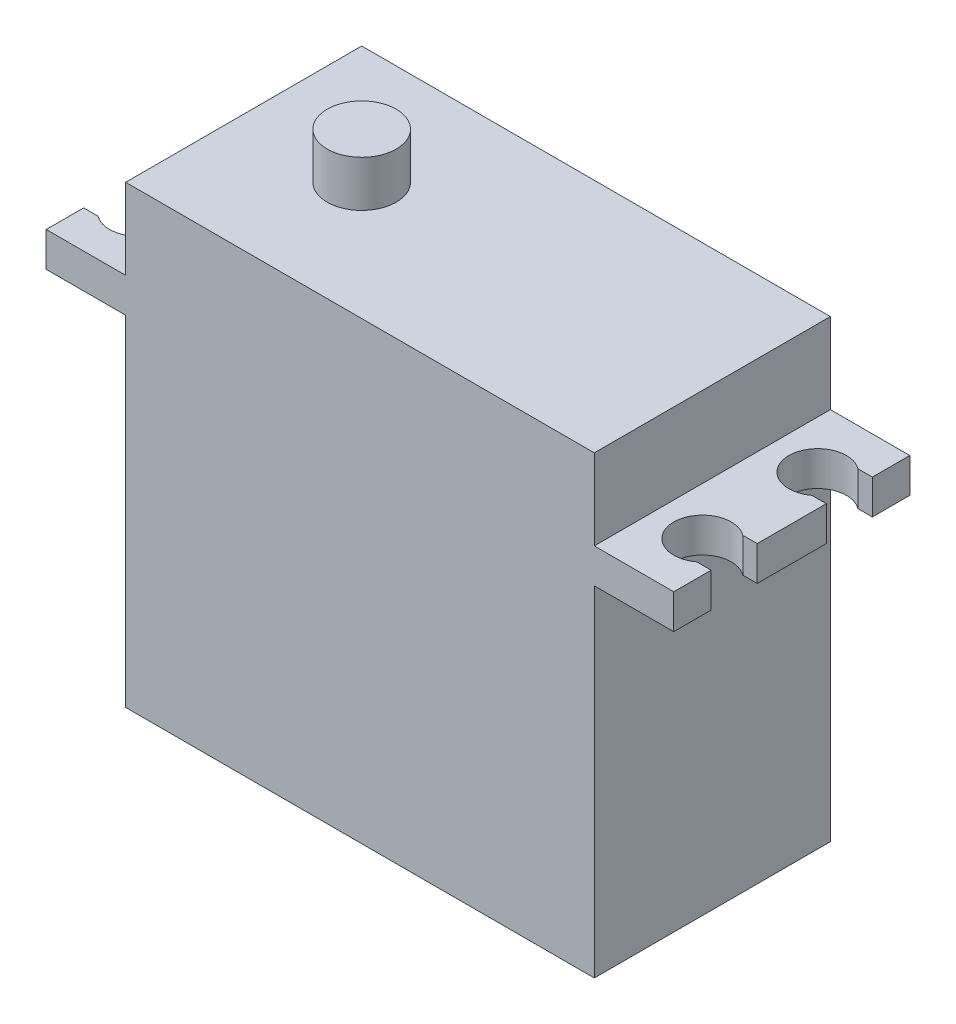
SolidWorks part; units mm, degrees
ref_plane "Front Plane" through (0, 0, 0) normal (0, 0, 1) x (1, 0, 0)
ref_plane "Top Plane" through (0, 0, 0) normal (0, 1, 0) x (1, 0, 0)
ref_plane "Right Plane" through (0, 0, 0) normal (1, 0, 0) x (0, 0, -1)
sketch "Sketch1" plane through (0, 0, 0) normal (0, 1, 0) x (1, 0, 0)
  line L1 (0, 0) -> (40.7, 0)
  line L2 (0, 0) -> (0, 20.5)
  line L3 (0, 20.5) -> (40.7, 20.5)
  line L4 (40.7, 0) -> (40.7, 20.5)
  dimension "D1" = 40.7
  dimension "D2" = 20.5
extrude "Boss-Extrude1" add sketch "Sketch1" along normal blind 39.5
sketch "Sketch2" plane through (0, 39.5, 0) normal (0, 1, 0) x (1, 0, 0)
  line L0 (0, 20.5) -> (0, 0) construction
  line L1 (40.7, 20.5) -> (0, 20.5) construction
  circle A0 centre (10.25, 10.25) radius 3
  dimension "D3" = 6
  dimension "D1" = 10.25
  dimension "D2" = 10.25
extrude "Boss-Extrude2" add sketch "Sketch2" along normal offset from surface (4 mm away) 43.5 up to face at (20.35, 0, -10.25)
ref_plane "Plane1" through (0, 29.5, 0) normal (0, 1, 0) x (1, 0, 0)
sketch "Sketch3" plane through (0, 29.5, 0) normal (0, 1, 0) x (1, 0, 0)
  line L0 (40.7, 20.5) -> (0, 20.5) construction
  line L1 (-6.9, 20.5) -> (47.6, 20.5)
  line L2 (-6.9, 20.5) -> (-6.9, 0)
  line L3 (-6.9, 0) -> (47.6, 0)
  line L4 (47.6, 20.5) -> (47.6, 0)
  line L5 (0, 0) -> (40.7, 0) construction
  point P8 (20.35, 0)
  point P9 (20.35, 0)
  dimension "D1" = 54.5
extrude "Boss-Extrude3" add sketch "Sketch3" along normal blind 3
sketch "Sketch4" plane through (0, 29.5, 0) normal (0, 1, 0) x (1, 0, 0)
  line L1 (40.7, 20.5) -> (0, 20.5) construction
  line L2 (-5.65, 17.25) -> (-6.9, 17.25)
  line L3 (-6.9, 20.5) -> (-6.9, 0) construction
  line L4 (-6.9, 17.25) -> (-6.9, 13.25)
  line L5 (-6.9, 13.25) -> (-5.65, 13.25)
  circle A0 centre (10.25, 10.25) radius 3 construction
  arc A2 (-5.65, 13.25) -> (-5.65, 17.25) centre (-4.15, 15.25) ccw
  point P15 (20.35, 20.5)
  dimension "D4" = 5
  dimension "D6" = 24.5
  dimension "D1" = 5
  dimension "D7" = 4
  dimension "D8" = 2
extrude "Cut-Extrude1" cut sketch "Sketch4" along normal through all
ref_plane "Plane2" through (0, 0, -10.25) normal (0, 0, -1) x (-1, 0, 0)
ref_plane "Plane3" through (20.35, 0, 0) normal (1, 0, 0) x (0, 0, -1)
mirror "Mirror1" about plane through (0, 0, -10.25) normal (0, 0, -1) of "Cut-Extrude1"
mirror "Mirror2" about plane through (20.35, 0, 0) normal (1, 0, 0) of "Mirror1", "Cut-Extrude1"
